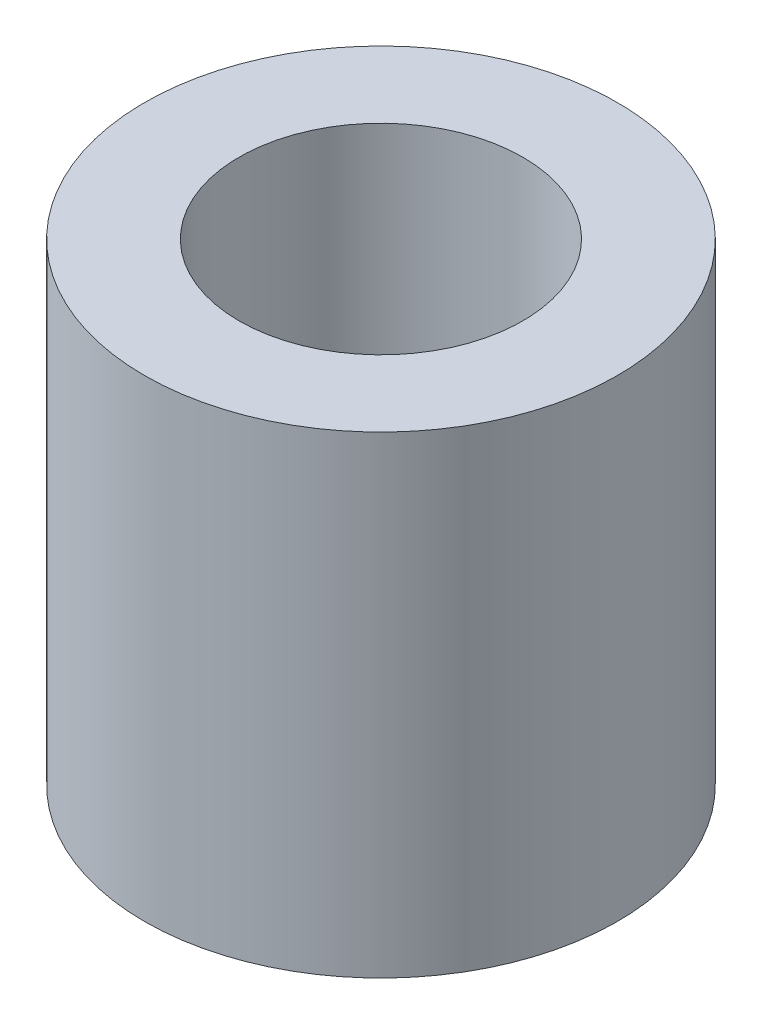
SolidWorks part; units mm, degrees
ref_plane "Front Plane" through (0, 0, 0) normal (0, 0, 1) x (1, 0, 0)
ref_plane "Top Plane" through (0, 0, 0) normal (0, 1, 0) x (1, 0, 0)
ref_plane "Right Plane" through (0, 0, 0) normal (1, 0, 0) x (0, 0, -1)
sketch "Sketch1" plane through (0, 0, 0) normal (0, 1, 0) x (1, 0, 0)
  circle A0 centre (0, 0) radius 1.5
  circle A1 centre (0, 0) radius 2.5
  dimension "D1" = 3
  dimension "D2" = 5
extrude "Boss-Extrude1" add sketch "Sketch1" along normal blind 5
